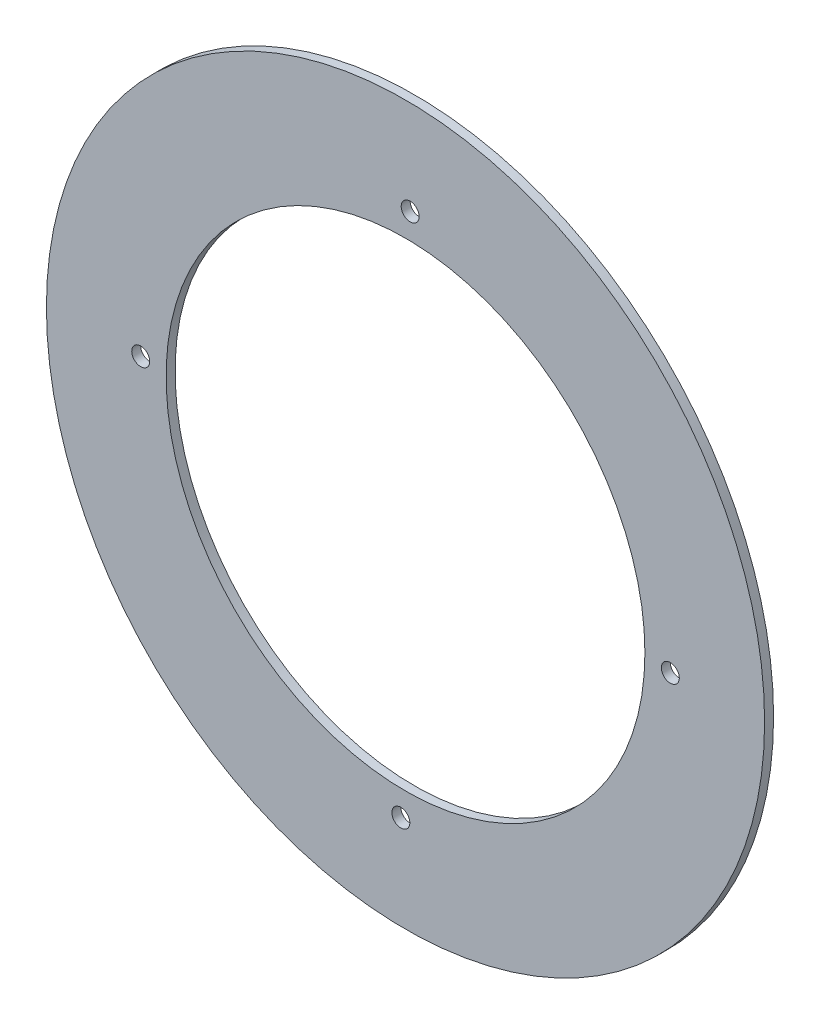
SolidWorks part; units mm, degrees
ref_plane "前视基准面" through (0, 0, 0) normal (0, 0, 1) x (1, 0, 0)
ref_plane "上视基准面" through (0, 0, 0) normal (0, 1, 0) x (1, 0, 0)
ref_plane "右视基准面" through (0, 0, 0) normal (1, 0, 0) x (0, 0, -1)
sketch "草图1" plane through (0, 0, 0) normal (0, 0, 1) x (1, 0, 0)
  circle A0 centre (0, 0) radius 60
  circle A1 centre (0, 0) radius 40
extrude "凸台-拉伸1" add sketch "草图1" along normal blind 1.5
sketch "草图2" plane through (0, 0, 0) normal (0, 0, -1) x (-1, 0, 0)
  circle A0 centre (-44.2431, -0.7793) radius 1.5
  circle A1 centre (-0.7793, 44.2431) radius 1.5
  circle A2 centre (44.2431, 0.7793) radius 1.5
  circle A3 centre (0.7793, -44.2431) radius 1.5
  dimension "D1" = 4
extrude "切除-拉伸2" cut sketch "草图2" against normal blind 2
